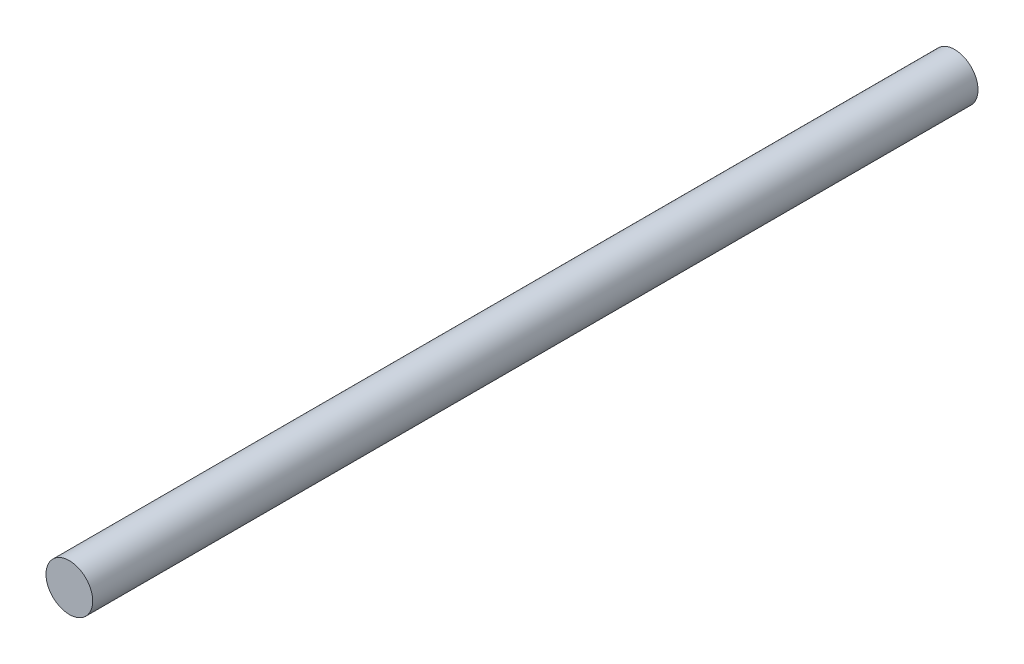
SolidWorks part; units mm, degrees
ref_plane "Front" through (0, 0, 0) normal (0, 0, 1) x (1, 0, 0)
ref_plane "Top" through (0, 0, 0) normal (0, 1, 0) x (1, 0, 0)
ref_plane "Right" through (0, 0, 0) normal (1, 0, 0) x (0, 0, -1)
sketch "Sketch1" plane through (0, 0, 0) normal (0, 0, 1) x (1, 0, 0)
  circle A0 centre (0, 0) radius 2.5
extrude "Boss-Extrude1" add sketch "Sketch1" along normal blind 304.8
sketch "For Drawing" plane through (0, 0, 0) normal (0, 0, 1) x (1, 0, 0)
  circle A0 centre (0, 0) radius 2.5
  circle A1 centre (0, 0) radius 2.5 construction
  dimension "Diameter" = 5
sketch "Break Point" plane through (0, 0, 0) normal (1, 0, 0) x (0, 0, -1)
  line L0 (-304.8, 0) -> (-297.3, 0)
  line L1 (-304.8, 2.5) -> (-304.8, -2.5) construction
  line L2 (0, 0) -> (-7.5, 0)
  line L3 (-7.5, -2.5) -> (-7.5, 2.5) construction
  line L4 (0, 2.5) -> (-304.8, 2.5) construction
  line L5 (-297.3, -2.5) -> (-297.3, 2.5) construction
  point P12 (-7.5, 0)
  point P15 (-297.3, 0)
  dimension "D1" = 7.5
sketch "Sketch2" plane through (0, 0, 304.8) normal (0, 0, 1) x (1, 0, 0)
  circle A0 centre (0, 0) radius 2.5 construction
  circle A1 centre (0, 0) radius 2.5
extrude "Cut-Extrude1" cut sketch "Sketch2" against normal blind 210
equation "\"D1@Break Point\"=\"Diameter@Sketch1\" * 1.5"
